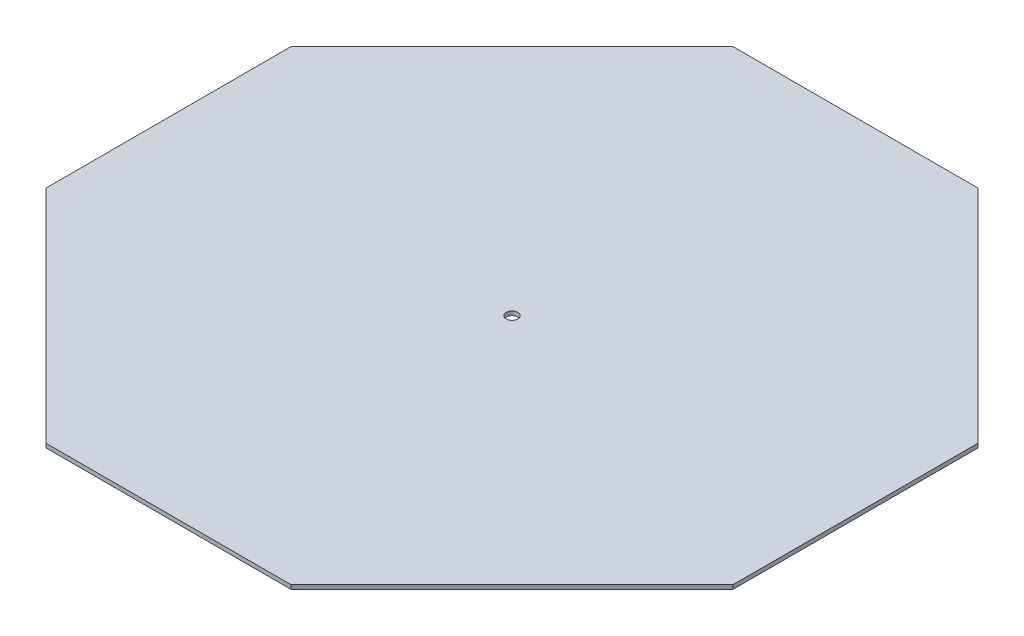
SolidWorks part; units mm, degrees
ref_plane "Front Plane" through (0, 0, 0) normal (0, 0, 1) x (1, 0, 0)
ref_plane "Top Plane" through (0, 0, 0) normal (0, 1, 0) x (1, 0, 0)
ref_plane "Right Plane" through (0, 0, 0) normal (1, 0, 0) x (0, 0, -1)
sketch "Sketch1" plane through (0, 0, 0) normal (0, 1, 0) x (1, 0, 0)
  line L0 (-89, 250) -> (89, 250) construction
  line L1 (89, 250) -> (250, 89) construction
  line L2 (250, 89) -> (250, -89) construction
  line L3 (250, -89) -> (89, -250) construction
  line L4 (89, -250) -> (-89, -250) construction
  line L5 (-89, -250) -> (-250, -89) construction
  line L6 (-250, -89) -> (-250, 89) construction
  line L7 (-250, 89) -> (-89, 250) construction
  line L8 (0, 250) -> (0, -250) construction
  line L9 (-250, 0) -> (250, 0) construction
  line L10 (-253, 90.2426) -> (-90.2426, 253)
  line L11 (-90.2426, 253) -> (90.2426, 253)
  line L12 (90.2426, 253) -> (253, 90.2426)
  line L13 (253, 90.2426) -> (253, -90.2426)
  line L14 (253, -90.2426) -> (90.2426, -253)
  line L15 (90.2426, -253) -> (-90.2426, -253)
  line L16 (-90.2426, -253) -> (-253, -90.2426)
  line L17 (-253, -90.2426) -> (-253, 90.2426)
  dimension "D1" = 500
  dimension "D2" = 178
  dimension "D3" = 3
extrude "Boss-Extrude1" add sketch "Sketch1" along normal blind 3
sketch "Sketch2" plane through (0, 3, 0) normal (0, 1, 0) x (1, 0, 0)
  circle A0 centre (0, 0) radius 4.25
  dimension "D1" = 8.5
extrude "Cut-Extrude1" cut sketch "Sketch2" against normal through all both
